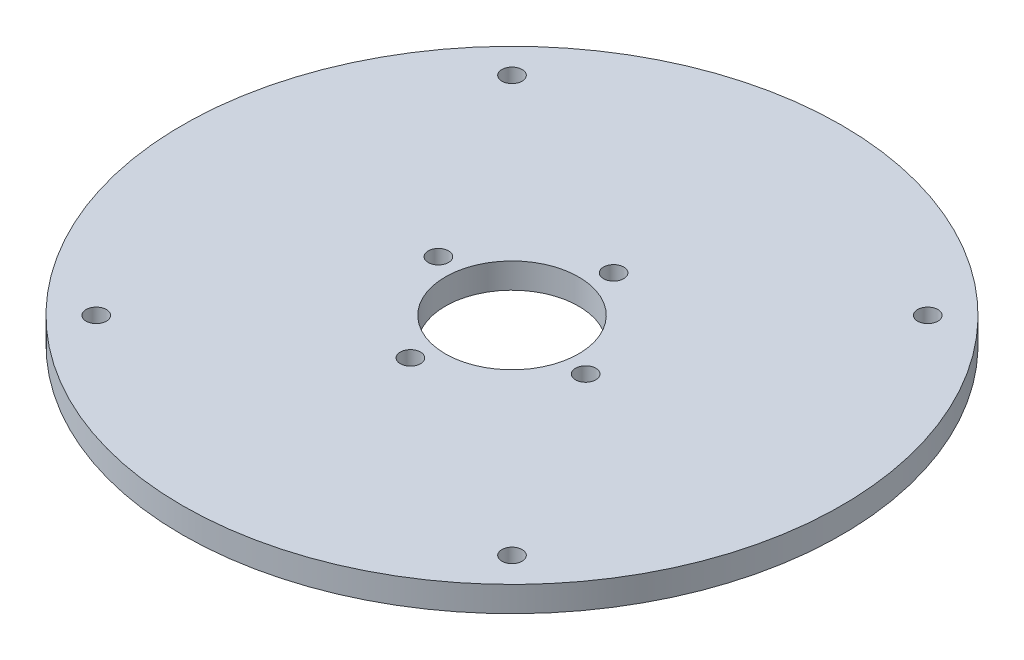
SolidWorks part; units mm, degrees
ref_plane "Front Plane" through (0, 0, 0) normal (0, 0, 1) x (1, 0, 0)
ref_plane "Top Plane" through (0, 0, 0) normal (0, 1, 0) x (1, 0, 0)
ref_plane "Right Plane" through (0, 0, 0) normal (1, 0, 0) x (0, 0, -1)
sketch "Sketch1" plane through (0, 0, 0) normal (0, 1, 0) x (1, 0, 0)
  circle A0 centre (0, 0) radius 65
  dimension "D1" = 130
extrude "Boss-Extrude1" add sketch "Sketch1" along normal blind 5
sketch "Sketch2" plane through (0, 5, 0) normal (0, 1, 0) x (1, 0, 0)
  line L0 (2.758, 17.2813) -> (-2.758, -17.2813) construction
  line L6 (-17.2813, 2.758) -> (17.2813, -2.758) construction
  circle A0 centre (0, 0) radius 13.15
  circle A1 centre (-17.2813, 2.758) radius 2
  circle A2 centre (2.758, 17.2813) radius 2
  circle A3 centre (17.2813, -2.758) radius 2
  circle A4 centre (-2.758, -17.2813) radius 2
  dimension "D1" = 26.3
  dimension "D2" = 4
  dimension "D3" = 4
  dimension "D4" = 4
  dimension "D5" = 4
extrude "Cut-Extrude1" cut sketch "Sketch2" against normal through all
sketch "Sketch4" plane through (0, 5, 0) normal (0, 1, 0) x (1, 0, 0)
  line L1 (-41, -41) -> (41, -41) construction
  line L2 (-41, -41) -> (-41, 41) construction
  line L3 (-41, 41) -> (41, 41) construction
  line L4 (41, -41) -> (41, 41) construction
  line L5 (-41, -41) -> (41, 41) construction
  line L6 (-41, 41) -> (41, -41) construction
  circle A0 centre (41, 41) radius 2
  circle A1 centre (41, -41) radius 2
  circle A2 centre (-41, -41) radius 2
  circle A3 centre (-41, 41) radius 2
  point P0 (0, 0)
  dimension "D3" = 4
  dimension "D4" = 4
  dimension "D5" = 4
  dimension "D6" = 4
  dimension "D1" = 82
  dimension "D2" = 82
extrude "Cut-Extrude2" cut sketch "Sketch4" against normal through all
